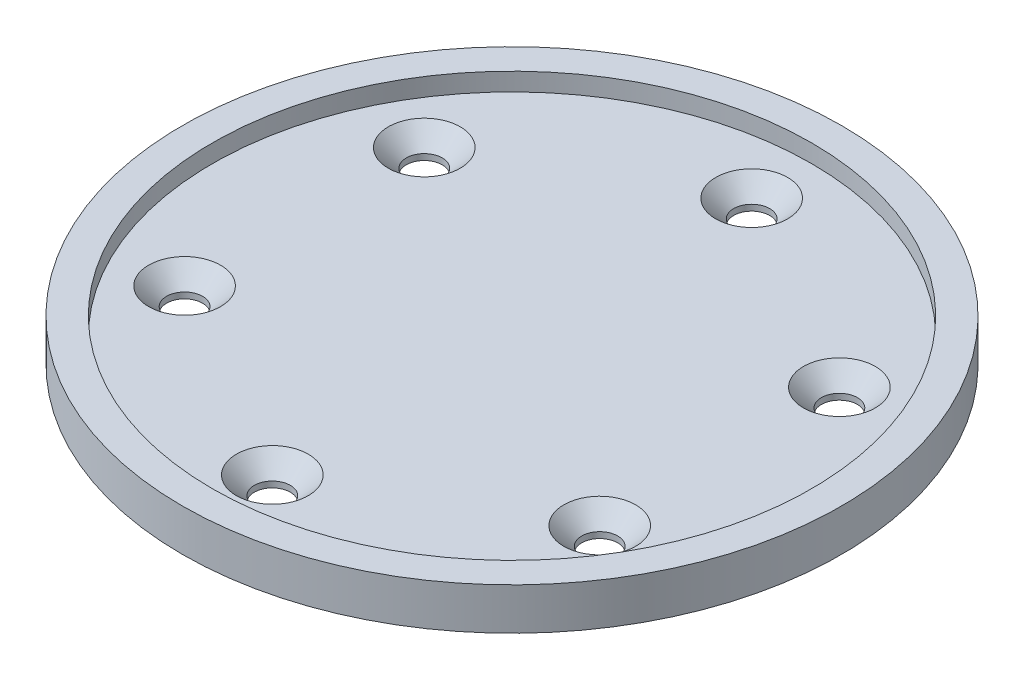
SolidWorks part; units mm, degrees
material "PBT General Purpose"
ref_plane "Front Plane" through (0, 0, 0) normal (0, 0, 1) x (1, 0, 0)
ref_plane "Top Plane" through (0, 0, 0) normal (0, 1, 0) x (1, 0, 0)
ref_plane "Right Plane" through (0, 0, 0) normal (1, 0, 0) x (0, 0, -1)
sketch "Sketch1" plane through (0, 0, 0) normal (0, 0, 1) x (1, 0, 0)
  line L0 (0, 0) -> (0, 21.4941) construction
  line L1 (50, 3.4786) -> (50, 6.4786)
  line L2 (50, 6.4786) -> (55, 6.4786)
  line L9 (50, 3.4786) -> (0, 3.4786)
  line L10 (0, -0.5214) -> (0, 3.4786)
  line L11 (0, -0.5214) -> (55, -0.5214)
  line L12 (55, -0.5214) -> (55, 6.4786)
  dimension "D1" = 0.5214
  dimension "D2" = 50
  dimension "D5" = 5
  dimension "D3" = 4
  dimension "D7" = 3
revolve "Revolve1" add sketch "Sketch1" angle 360 about L0
sketch "Sketch2" plane through (0, 3.4786, 0) normal (0, 1, 0) x (1, 0, 0)
  line L0 (0, 0) -> (0, 40) construction
  circle A0 centre (0, 40) radius 3
  circle A6 centre (34.641, 20) radius 3
  circle A7 centre (34.641, -20) radius 3
  circle A8 centre (0, -40) radius 3
  circle A9 centre (-34.641, -20) radius 3
  circle A10 centre (-34.641, 20) radius 3
  point P2 (0, 0)
  point P4 (34.641, 20)
  point P31 (0, 0)
  dimension "D1" = 6
  dimension "D2" = 40
  dimension "D3" = 6
extrude "Cut-Extrude1" cut sketch "Sketch2" against normal through all
chamfer "Chamfer1" distance 3 angle 45 6 edges at (0, 3.4786, -37) (34.641, 3.4786, -17) (34.641, 3.4786, 23) (0, 3.4786, 43) (-34.641, 3.4786, 23) (-34.641, 3.4786, -17)
sketch3d "3DSketch1"
  point P0 (-57, 29.4786, 57)
